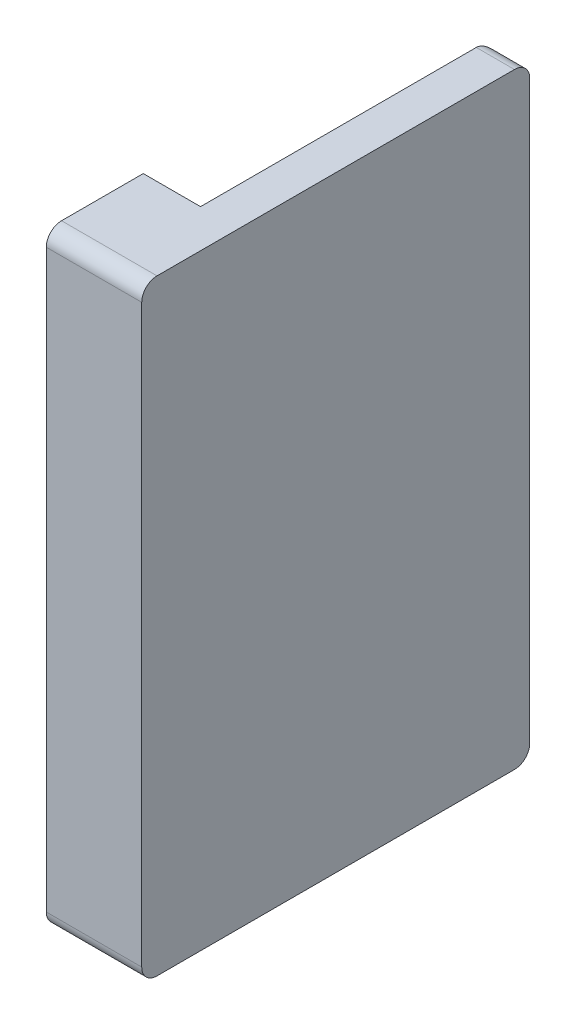
SolidWorks part; units mm, degrees
ref_plane "Front Plane" through (0, 0, 0) normal (0, 0, 1) x (1, 0, 0)
ref_plane "Top Plane" through (0, 0, 0) normal (0, 1, 0) x (1, 0, 0)
ref_plane "Right Plane" through (0, 0, 0) normal (1, 0, 0) x (0, 0, -1)
sketch "Sketch1" plane through (0, 0, 0) normal (0, 1, 0) x (1, 0, 0)
  line L1 (0, 0) -> (7.5, 0)
  line L2 (0, 0) -> (0, 12.7)
  line L3 (0, 12.7) -> (7.5, 12.7)
  line L4 (7.5, 0) -> (7.5, 12.7)
  line L5 (7.5, 0) -> (12.5, 0)
  line L6 (7.5, 0) -> (7.5, 50.8)
  line L7 (7.5, 50.8) -> (12.5, 50.8)
  line L8 (12.5, 0) -> (12.5, 50.8)
  dimension "D1" = 12.7
  dimension "D2" = 7.5
  dimension "D3" = 50.8
  dimension "D4" = 5
extrude "Boss-Extrude1" add sketch "Sketch1" along normal blind 79.375 contours L1 L4 L3 L2 | L5 L8 L7 L6 L4
fillet "Fillet1" radius 2 5 edges at (6.25, 0, 0) (6.25, 79.375, 0) (10, 0, -50.8) (10, 79.375, -50.8) (7.5, 39.6875, -50.8)
